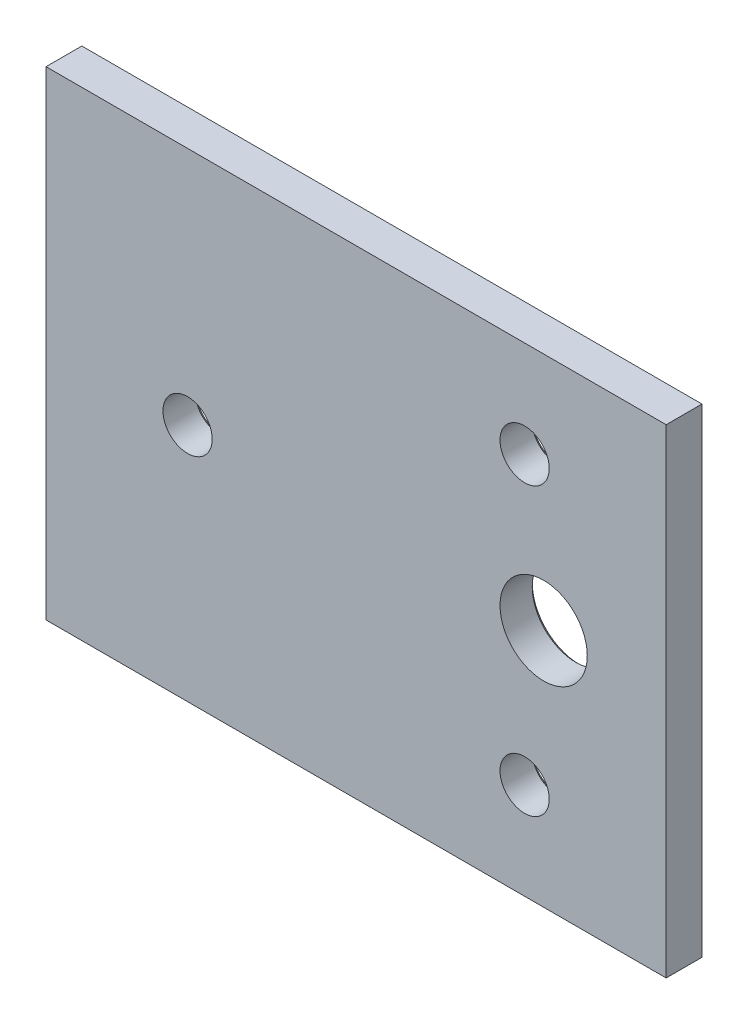
SolidWorks part; units mm, degrees
ref_plane "Plan de face" through (0, 0, 0) normal (0, 0, 1) x (1, 0, 0)
ref_plane "Plan de dessus" through (0, 0, 0) normal (0, 1, 0) x (1, 0, 0)
ref_plane "Plan de droite" through (0, 0, 0) normal (1, 0, 0) x (0, 0, -1)
sketch "Esquisse2" plane through (0, 0, 0) normal (0, 0, 1) x (1, 0, 0)
  line L1 (-55, 42.5) -> (55, 42.5)
  line L2 (-55, 42.5) -> (-55, -42.5)
  line L3 (-55, -42.5) -> (55, -42.5)
  line L4 (55, 42.5) -> (55, -42.5)
  line L5 (-55, 42.5) -> (55, -42.5) construction
  line L6 (-55, -42.5) -> (55, 42.5) construction
  point P0 (0, 0)
  dimension "D1" = 110
  dimension "D2" = 85
extrude "Boss.-Extru.1" add sketch "Esquisse2" along normal mid plane 6.35
sketch "Esquisse6" plane through (0, 0, -3.175) normal (0, 0, -1) x (-1, 0, 0)
  line L0 (-25.4, 42.5) -> (-25.4, -42.5) construction
  line L1 (-55, 42.5) -> (55, 42.5) construction
  line L2 (55, -42.5) -> (-55, -42.5) construction
  line L3 (25.4, 42.5) -> (25.4, -42.5) construction
  line L4 (-25.527, 0.453) -> (-25.527, 50000.453) construction
  line L6 (-25.4, 0) -> (25.4, 0) construction
  line L7 (-55, 42.5) -> (55, 42.5) construction
  line L8 (-55, -42.5) -> (-55, 42.5) construction
  point P14 (0, 0)
  dimension "D1" = 50.8
  dimension "D2" = 110
  dimension "D3" = 29.6
  dimension "D4" = 0.127
hole_wizard "5/16 Clearance Hole1" positions "Sketch1" profile "Sketch2" hole size "5/16" standard "ANSI Inch" end condition up to next
sketch "Sketch1" plane through (0, 0, -3.175) normal (0, 0, -1) x (-1, 0, 0)
  line L1 (-29.892, -1.7422) -> (-29.892, 49998.2578) construction
  line L3 (-200025.4, 0) -> (200025.4, 0) construction
  line L4 (25.4, 42.5) -> (25.4, -42.5) construction
  point P0 (-29.892, 25.4)
  point P2 (-29.892, -25.4)
  point P4 (29.892, 0)
  dimension "D2" = 4.492
  dimension "D3" = 50.8
  dimension "D4" = 25.4
sketch "Sketch2" plane through (29.892, 25.4, -3.175) normal (1, 0, 0) x (0, 1, 0)
  line L0 (0, 0) -> (0, 6.35)
  line L1 (0, 6.35) -> (4.365, 6.35)
  line L2 (4.365, 6.35) -> (4.365, 0.635)
  line L3 (4.365, 0.635) -> (5, 0)
  line L5 (5, 0) -> (0, 0)
  line L6 (-4.365, 0.635) -> (-5, 0) construction
  line L11 (0, -6.35) -> (0, 107.95) construction
  dimension "Thru Hole Dia." = 8.73
  dimension "Thru Hole Depth" = 6.35
  dimension "Near C'Sink Dia." = 10
  dimension "Near C'Sink Angle" = 90
hole_wizard "9/16 Clearance Hole1" positions "Sketch3" profile "Sketch4" hole size "9/16" standard "ANSI Inch" end condition up to next
sketch "Sketch3" plane through (0, 0, -3.175) normal (0, 0, -1) x (-1, 0, 0)
  line L0 (-200025.4, 0) -> (200025.4, 0) construction
  line L1 (-25.4, 42.5) -> (-25.4, -42.5) construction
  point P0 (-33.2664, 0)
  dimension "D1" = 7.8664
sketch "Sketch4" plane through (33.2664, 0, -3.175) normal (1, 0, 0) x (0, 1, 0)
  line L0 (0, 0) -> (0, 6.35)
  line L1 (0, 6.35) -> (7.7394, 6.35)
  line L2 (7.7394, 6.35) -> (7.7394, 0.635)
  line L3 (7.7394, 0.635) -> (8.3744, 0)
  line L5 (8.3744, 0) -> (0, 0)
  line L6 (-7.7394, 0.635) -> (-8.3744, 0) construction
  line L11 (0, -6.35) -> (0, 107.95) construction
  dimension "Thru Hole Dia." = 15.4788
  dimension "Thru Hole Depth" = 6.35
  dimension "Near C'Sink Dia." = 16.7488
  dimension "Near C'Sink Angle" = 90
equation "\"D4@Sketch1\"=\"D3@Sketch1\"/2"
equation "\"D1@Sketch3\"=0.609400in/2 + 0.005in"
equation "\"D3@Esquisse6\"=(\"D2@Esquisse6\"-\"D1@Esquisse6\")/2"
